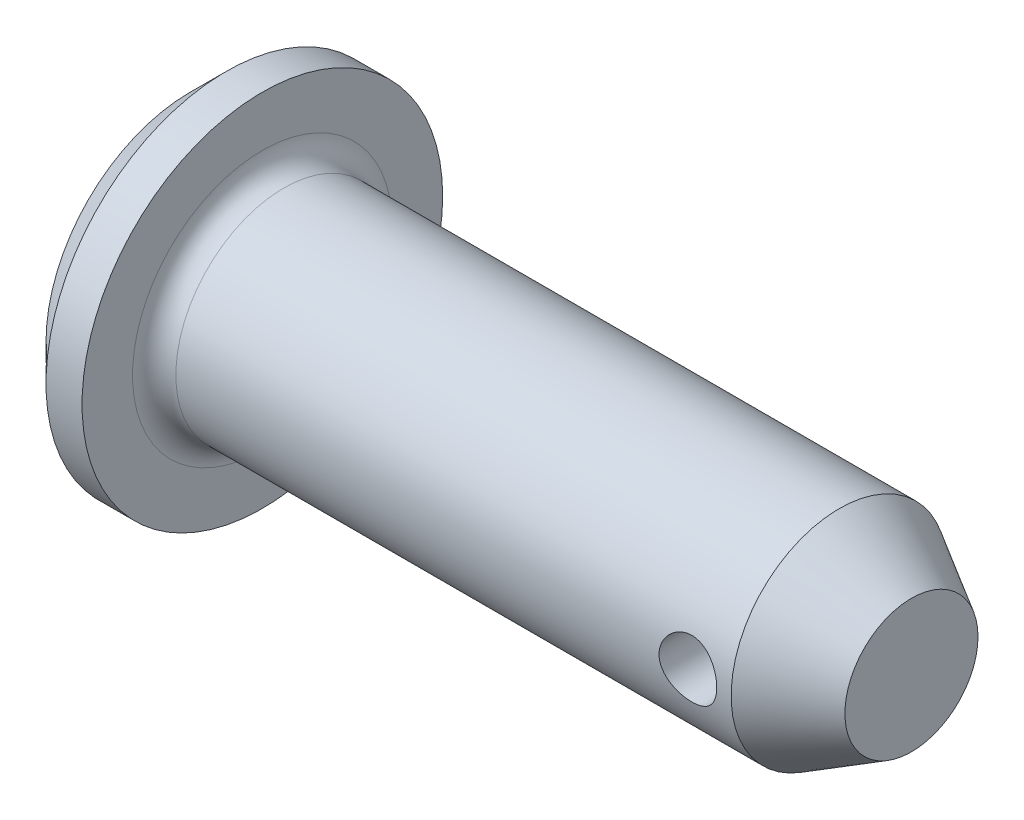
SolidWorks part; units mm, degrees
ref_plane "前视" through (0, 0, 0) normal (0, 0, 1) x (1, 0, 0)
ref_plane "上视" through (0, 0, 0) normal (0, 1, 0) x (1, 0, 0)
ref_plane "右视" through (0, 0, 0) normal (1, 0, 0) x (0, 0, -1)
sketch "尺寸草图" plane through (0, 0, 0) normal (0, 0, 1) x (1, 0, 0)
  line L0 (0, 10) -> (0, 0)
  line L1 (0, 0) -> (18, 0)
  circle A0 centre (14.8, 0) radius 0.8 construction
  point P3 (0, 6)
  point P5 (2, 0)
  point P6 (0.6, 0)
  point P7 (16, 0)
  point P8 (3, 0)
  dimension "d1" = 1.6
  dimension "l" = 18
  dimension "dk" = 10
  dimension "d" = 6
  dimension "k" = 2
  dimension "r" = 0.6
  dimension "c" = 2
  dimension "e" = 1
  dimension "le" = 3.2
sketch "草图1" plane through (0, 0, 0) normal (0, 0, 1) x (1, 0, 0)
  line L0 (0, 0) -> (-7.3443, 0) construction
  line L1 (0, 0) -> (20, 0)
  line L2 (0, 0) -> (0, 4)
  line L3 (1, 5) -> (2, 5)
  line L4 (2, 5) -> (2, 3)
  line L5 (2, 3) -> (20, 3)
  line L6 (20, 3) -> (20, 0)
  line L7 (0, 4) -> (1, 5)
  point P4 (0, 5)
  dimension "D2" = 10
  dimension "D1" = 18
  dimension "D3" = 6
  dimension "D4" = 2
revolve "基体-旋转" add sketch "草图1" angle 360 about L0
sketch "草图2" plane through (0, 0, 0) normal (0, 0, 1) x (1, 0, 0)
  line L0 (0, 0) -> (18, 0) construction
  line L1 (20, -3) -> (20, 3) construction
  circle A1 centre (16.8, 0) radius 0.8
  dimension "D1" = 1.6
  dimension "D2" = 3.2
extrude "切除-拉伸1" cut sketch "草图2" against normal through all and the other way through all
fillet "圆角1" radius 0.6 1 edges at (2, 0, -3)
chamfer "倒角1" distance 2 angle 30 1 edges at (20, 0, -3)
